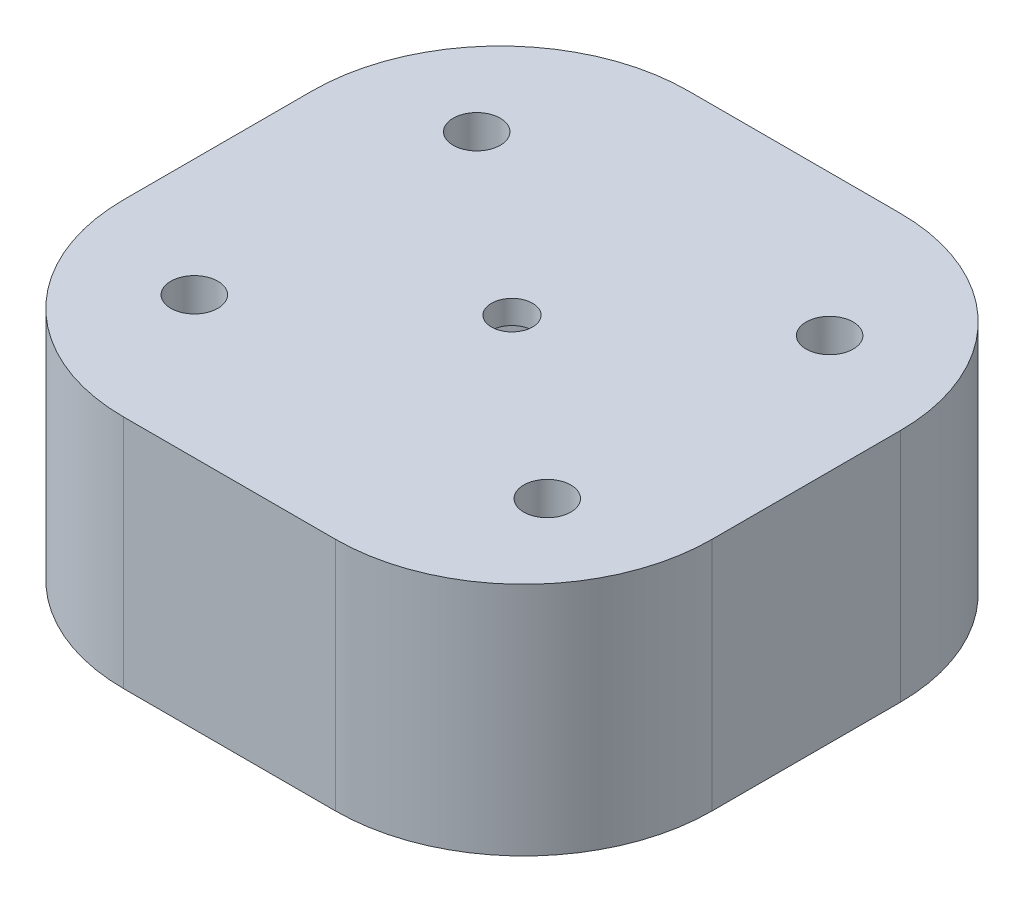
SolidWorks part; units mm, degrees
ref_plane "Front Plane" through (0, 0, 0) normal (0, 0, 1) x (1, 0, 0)
ref_plane "Top Plane" through (0, 0, 0) normal (0, 1, 0) x (1, 0, 0)
ref_plane "Right Plane" through (0, 0, 0) normal (1, 0, 0) x (0, 0, -1)
sketch "Sketch1" plane through (0, 0, 0) normal (0, 1, 0) x (1, 0, 0)
  line L0 (0, 24) -> (0, -24) construction
  line L1 (-9, 24) -> (9, 24)
  line L2 (25, 8) -> (25, -8)
  line L3 (9, -24) -> (-9, -24)
  line L4 (-25, -8) -> (-25, 8)
  line L5 (-25, 0) -> (25, 0) construction
  line L7 (0, 7.2169) -> (-6.25, 3.6084)
  line L8 (-6.25, 3.6084) -> (-6.25, -3.6084)
  line L9 (-6.25, -3.6084) -> (0, -7.2169)
  line L10 (0, -7.2169) -> (6.25, -3.6084)
  line L11 (6.25, -3.6084) -> (6.25, 3.6084)
  line L12 (6.25, 3.6084) -> (0, 7.2169)
  arc A0 (-25, -8) -> (-9, -24) centre (-9, -8) ccw
  arc A1 (9, -24) -> (25, -8) centre (9, -8) ccw
  arc A2 (25, 8) -> (9, 24) centre (9, 8) ccw
  arc A3 (-25, 8) -> (-9, 24) centre (-9, 8) cw
  circle A8 centre (0, 0) radius 6.25 construction
  point P2 (0, 0)
  dimension "D1" = 18
  dimension "D2" = 48
  dimension "D3" = 50
  dimension "D4" = 12.5
extrude "Boss-Extrude1" add sketch "Sketch1" along normal blind 18
sketch "Sketch2" plane through (0, 18, 0) normal (0, 1, 0) x (1, 0, 0)
  line L0 (0, 24) -> (0, -24) construction
  line L1 (-9, 24) -> (9, 24)
  line L2 (25, 8) -> (25, -8)
  line L3 (9, -24) -> (-9, -24)
  line L4 (-25, -8) -> (-25, 8)
  line L5 (-25, 0) -> (25, 0) construction
  arc A0 (-25, -8) -> (-9, -24) centre (-9, -8) ccw
  arc A1 (9, -24) -> (25, -8) centre (9, -8) ccw
  arc A2 (25, 8) -> (9, 24) centre (9, 8) ccw
  arc A3 (-25, 8) -> (-9, 24) centre (-9, 8) cw
  circle A4 centre (-15, 12) radius 2
  circle A5 centre (15, 12) radius 2
  circle A6 centre (15, -12) radius 2
  circle A7 centre (-15, -12) radius 2
  circle A8 centre (0, 0) radius 1.75
  point P2 (0, 0)
  dimension "D1" = 4
  dimension "D2" = 4
  dimension "D3" = 4
  dimension "D4" = 3.5
extrude "Boss-Extrude3" add sketch "Sketch2" along normal blind 2
sketch "Sketch3" plane through (0, 20, 0) normal (0, 1, 0) x (1, 0, 0)
  circle A0 centre (-15, 12) radius 2
  circle A1 centre (15, 12) radius 2
  circle A2 centre (15, -12) radius 2
  circle A3 centre (-15, -12) radius 2
extrude "Cut-Extrude1" cut sketch "Sketch3" against normal blind 10
